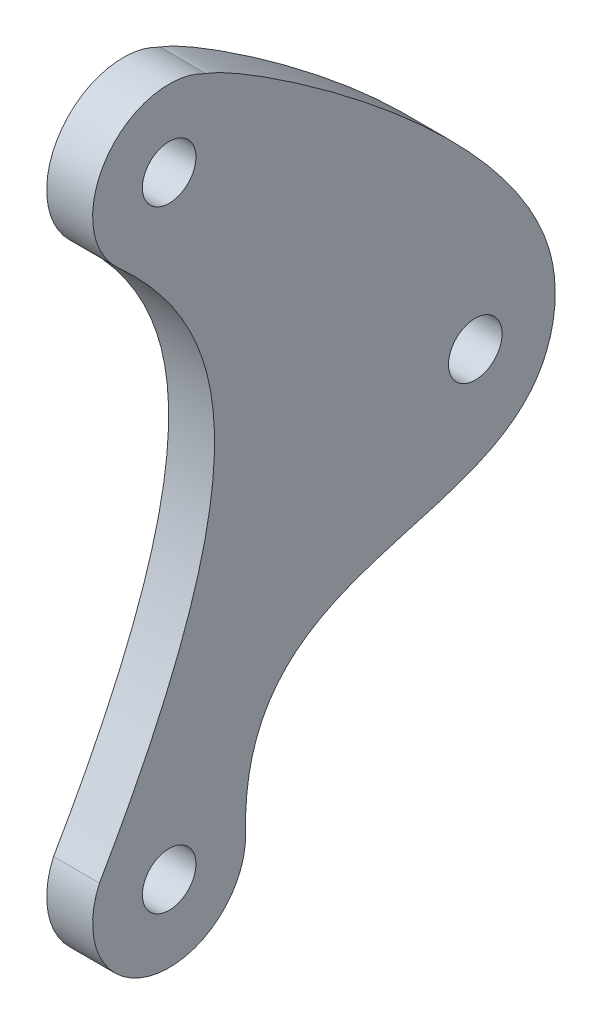
SolidWorks part; units mm, degrees
ref_plane "Alzado" through (0, 0, 0) normal (0, 0, 1) x (1, 0, 0)
ref_plane "Planta" through (0, 0, 0) normal (0, 1, 0) x (1, 0, 0)
ref_plane "Vista lateral" through (0, 0, 0) normal (1, 0, 0) x (0, 0, -1)
sketch "Croquis1" plane through (0, 0, 0) normal (1, 0, 0) x (0, 0, -1)
  line L0 (-20, 20) -> (0, 20) construction
  line L1 (-20, 20) -> (0, 0) construction
  line L2 (0, 20) -> (0, 0) construction
  line L4 (0, 0) -> (-5.5778, 0) construction
  line L5 (0, 0) -> (-20, -20) construction
  line L9 (0, 0) -> (0, -20) construction
  line L10 (0, -20) -> (-20, -20) construction
  arc A0 (-24.5523, -17.9321) -> (-15, -20) centre (-20, -20) ccw
  arc A1 (-17.5522, 24.3598) -> (-23.5071, 16.4362) centre (-20, 20) ccw
  circle A4 centre (-20, 20) radius 1.75
  circle A5 centre (0, 0) radius 1.75
  circle A6 centre (-20, -20) radius 1.75
  spline S0 degree 3 poles (-15, -20) (-15.4668, -5.271) (3.8979, -11.6689) (6.6486, 9.648) (-15.5632, 23.8969) (-17.5522, 24.3598) knots 0 0 0 0 0.482956 0.582956 1 1 1 1
  spline S1 degree 3 poles (-24.5523, -17.9321) (-13.483, 1.1936) (-15.9412, 9.6123) (-23.5071, 16.4362) knots 0 0 0 0 1 1 1 1
  dimension "D1" = 20
  dimension "D5" = 5
  dimension "D3" = 20
  dimension "D6" = 5
  dimension "D7" = 3.5
  dimension "D8" = 3.5
  dimension "D2" = 20
  dimension "D4" = 20
extrude "Saliente-Extruir2" add sketch "Croquis1" along normal blind 3
